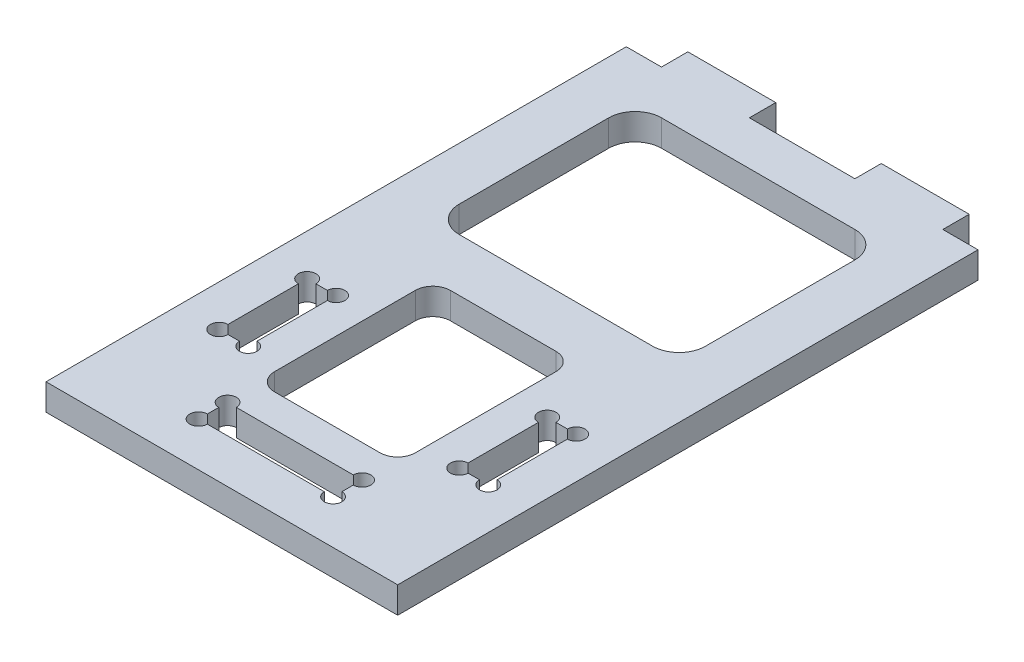
SolidWorks part; units mm, degrees
ref_plane "前视基准面" through (0, 0, 0) normal (0, 0, 1) x (1, 0, 0)
ref_plane "上视基准面" through (0, 0, 0) normal (0, 1, 0) x (1, 0, 0)
ref_plane "右视基准面" through (0, 0, 0) normal (1, 0, 0) x (0, 0, -1)
other "Configuration Table"
sketch "草图1" plane through (0, 0, 0) normal (0, 1, 0) x (1, 0, 0)
  line L0 (0, 19.586) -> (0, -14.3312) construction
  line L1 (-20, 18) -> (20, 18)
  line L2 (-20, 18) -> (-20, -18)
  line L3 (-20, -18) -> (20, -18)
  line L4 (20, 18) -> (20, -18)
  line L5 (-20, 18) -> (20, -18) construction
  line L6 (-20, -18) -> (20, 18) construction
  line L7 (-7.65, -9.7) -> (7.65, -9.7)
  line L8 (-7.65, -9.7) -> (-7.65, -13)
  line L9 (-7.65, -13) -> (7.65, -13)
  line L10 (7.65, -9.7) -> (7.65, -13)
  line L11 (-7.65, -9.7) -> (7.65, -13) construction
  line L12 (-7.65, -13) -> (7.65, -9.7) construction
  line L13 (-15.3, 7) -> (-12, 7)
  line L14 (-15.3, 7) -> (-15.3, -3)
  line L15 (-15.3, -3) -> (-12, -3)
  line L16 (-12, 7) -> (-12, -3)
  line L17 (15.3, -3) -> (12, -3)
  line L18 (12, 7) -> (12, -3)
  line L19 (15.3, 7) -> (12, 7)
  line L20 (15.3, 7) -> (15.3, -3)
  line L21 (-15.3, 2) -> (-10.0667, 2) construction
  line L22 (-15.3, -3) -> (-12, -3)
  line L23 (15.3, -3) -> (12, -3)
  line L24 (12, 7) -> (12, -3)
  line L25 (15.3, -3) -> (12, -3)
  line L26 (15.3, 7) -> (15.3, -3)
  line L27 (15.3, 7) -> (12, 7)
  line L28 (16, 51) -> (6, 51)
  line L29 (-20, 18) -> (20, 18)
  line L30 (-20, 18) -> (-20, 48)
  line L31 (-20, 48) -> (20, 48)
  line L32 (20, 18) -> (20, 48)
  line L33 (-16, 48) -> (-6, 48)
  line L34 (-16, 48) -> (-16, 51)
  line L35 (-16, 51) -> (-6, 51)
  line L36 (-6, 48) -> (-6, 51)
  line L37 (6, 48) -> (6, 51)
  line L38 (16, 48) -> (6, 48)
  line L39 (16, 48) -> (16, 51)
  circle A0 centre (0, 18) radius 20
  circle A1 centre (0, 25.3) radius 4.2
  circle A2 centre (-15.3, 7) radius 1
  circle A3 centre (-12, 7) radius 1
  circle A4 centre (-12, -3) radius 1
  circle A5 centre (-15.3, -3) radius 1
  circle A6 centre (15.3, -3) radius 1
  circle A7 centre (12, -3) radius 1
  circle A8 centre (12, 7) radius 1
  circle A9 centre (15.3, 7) radius 1
  circle A10 centre (-7.65, -9.7) radius 1
  circle A11 centre (7.65, -9.7) radius 1
  circle A12 centre (7.65, -13) radius 1
  circle A13 centre (-7.65, -13) radius 1
  point P0 (0, 0)
  point P11 (0, -11.35)
  dimension "D3" = 8.4
  dimension "D4" = 25.3
  dimension "D12" = 2
  dimension "D1" = 40
  dimension "D2" = 36
  dimension "D5" = 3.3
  dimension "D6" = 15.3
  dimension "D7" = 5
  dimension "D8" = 3.3
  dimension "D9" = 10
  dimension "D10" = 12
  dimension "D11" = 15
  dimension "D13" = 30
  dimension "D14" = 3
  dimension "D15" = 10
  dimension "D16" = 6
extrude "凸台-拉伸1" add sketch "草图1" along normal blind 3 contours A0 L2 L3 L4 A13 L8 A10 L7 A11 L10 A12 L9 L22 A5 L14 A2 L13 A3 L16 A4 L27 A9 L26 A6 L25 A7 L24 A8 | L1 A0 | L1 A0 A1 | A0 L32 L31 L30 | L31 L36 L35 L34 | L31 L39 L28 L37 | L29 A1 | L29 A1
sketch "草图2" plane through (0, 3, 0) normal (0, 1, 0) x (1, 0, 0)
  line L1 (-8, 14) -> (8, 14)
  line L2 (-8, 14) -> (-8, -6)
  line L3 (-8, -6) -> (8, -6)
  line L4 (8, 14) -> (8, -6)
  line L5 (-8, 14) -> (8, -6) construction
  line L6 (-8, -6) -> (8, 14) construction
  point P0 (0, 4)
  dimension "D1" = 20
  dimension "D2" = 16
  dimension "D3" = 4
extrude "切除-拉伸1" cut sketch "草图2" against normal through all both and the other way through all
fillet "圆角1" radius 2 4 edges at (-8, 1.5, 6) (8, 1.5, 6) (8, 1.5, -14) (-8, 1.5, -14)
sketch "草图3" plane through (0, 3, 0) normal (0, 1, 0) x (1, 0, 0)
  line L0 (6, 14) -> (-6, 14) construction
  line L1 (-14, 43) -> (14, 43)
  line L2 (-14, 43) -> (-14, 20)
  line L3 (-14, 20) -> (14, 20)
  line L4 (14, 43) -> (14, 20)
  line L5 (-14, 43) -> (14, 20) construction
  line L6 (-14, 20) -> (14, 43) construction
  point P0 (0, 31.5)
  point P5 (0, 0)
  dimension "D1" = 23
  dimension "D2" = 28
  dimension "D3" = 6
extrude "切除-拉伸2" cut sketch "草图3" against normal blind 10
fillet "圆角2" radius 3 4 edges at (-14, 1.5, -20) (14, 1.5, -20) (14, 1.5, -43) (-14, 1.5, -43)
